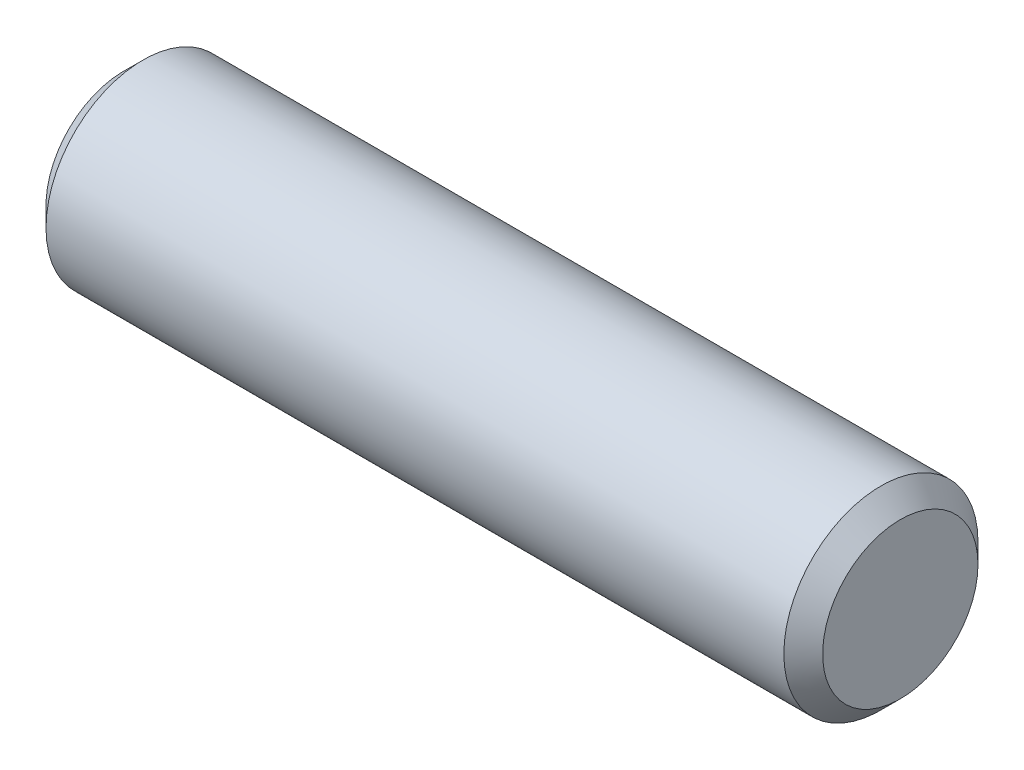
SolidWorks part; units mm, degrees
material "Plain Carbon Steel"
ref_plane "Front" through (0, 0, 0) normal (0, 0, 1) x (1, 0, 0)
ref_plane "Top" through (0, 0, 0) normal (0, 1, 0) x (1, 0, 0)
ref_plane "Right" through (0, 0, 0) normal (1, 0, 0) x (0, 0, -1)
sketch "Sketch1" plane through (0, 0, 0) normal (0, 0, 1) x (1, 0, 0)
  line L0 (-6.35, 0) -> (6.35, 0) construction
  line L1 (6.35, 1.5875) -> (6.35, -1.5875) construction
  line L2 (-6.35, 1.5875) -> (-6.35, -1.5875) construction
  dimension "Length" = 12.7
  dimension "Diameter" = 3.175
sketch "Sketch2" plane through (0, 0, 0) normal (1, 0, 0) x (0, 0, -1)
  circle A0 centre (0, 0) radius 1.5875
extrude "Extrude1" add sketch "Sketch2" against normal up to vertex (6.35 mm away) and the other way up to vertex (6.35 mm away) up to point (-6.35, 1.5875, 0) other way up to point (6.35, 1.5875, 0)
chamfer "Chamfer1" distance 0.3175 angle 45 2 edges at (6.35, 0, -1.5875) (-6.35, 0, -1.5875)
equation "\"D1@Chamfer1\" = \"Diameter@Sketch1\"*.1"
